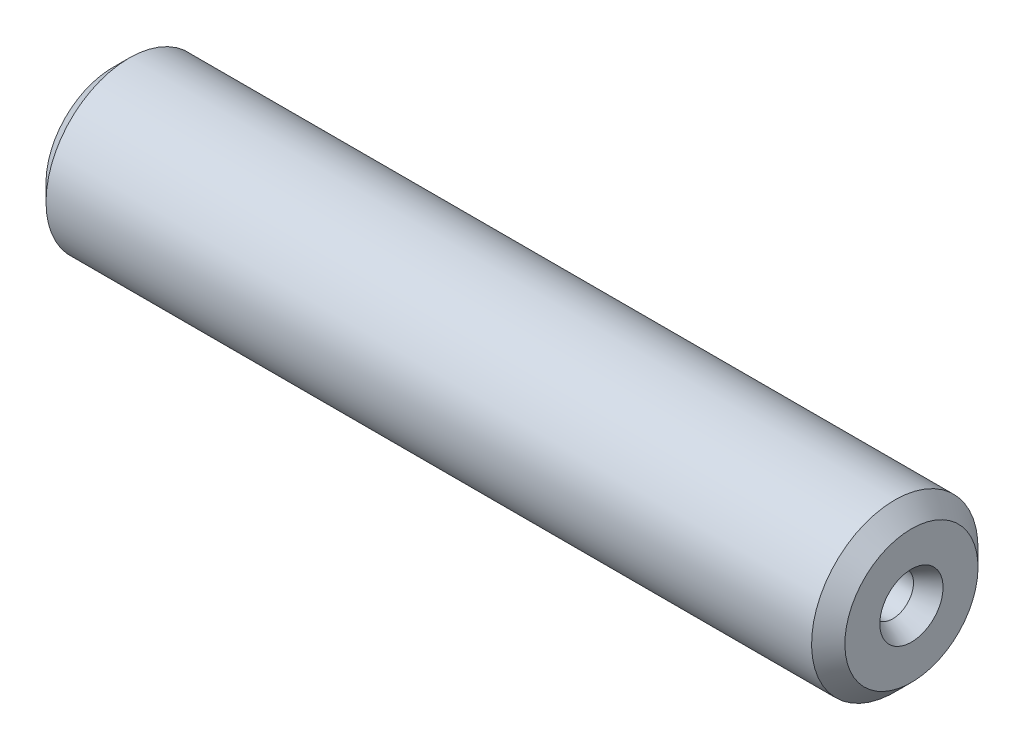
SolidWorks part; units mm, degrees
material "4140"
ref_plane "Front Plane" through (0, 0, 0) normal (0, 0, 1) x (1, 0, 0)
ref_plane "Top Plane" through (0, 0, 0) normal (0, 1, 0) x (1, 0, 0)
ref_plane "Right Plane" through (0, 0, 0) normal (1, 0, 0) x (0, 0, -1)
sketch "Sketch1" plane through (0, 0, 0) normal (0, 0, 1) x (1, 0, 0)
  line L0 (0, 1.9) -> (0, 5)
  line L1 (0, 5) -> (-48, 5)
  line L2 (-48, 5) -> (-48, 0)
  line L3 (0, 0) -> (-48, 0) construction
  line L4 (-4, 0) -> (-48, 0)
  line L5 (0, 1.9) -> (-1.1258, 1.25)
  line L6 (-1.1258, 1.25) -> (-3.2489, 1.25)
  line L7 (-3.2489, 1.25) -> (-4, 0)
  line L8 (-1.1258, 1.25) -> (-3.2909, 0) construction
  dimension "D1" = 48
  dimension "D2" = 10
  dimension "D3" = 59
  dimension "D4" = 2.5
  dimension "D5" = 30
  dimension "D6" = 3.8
  dimension "D7" = 4
revolve "Revolve1" add sketch "Sketch1" angle 360 about L3
cosmetic thread "Cosmetic Thread1"
cosmetic thread "Cosmetic Thread2"
chamfer "Chamfer1" distance 1 angle 45 2 edges at (-48, 5, 0) (0, 5, 0)
